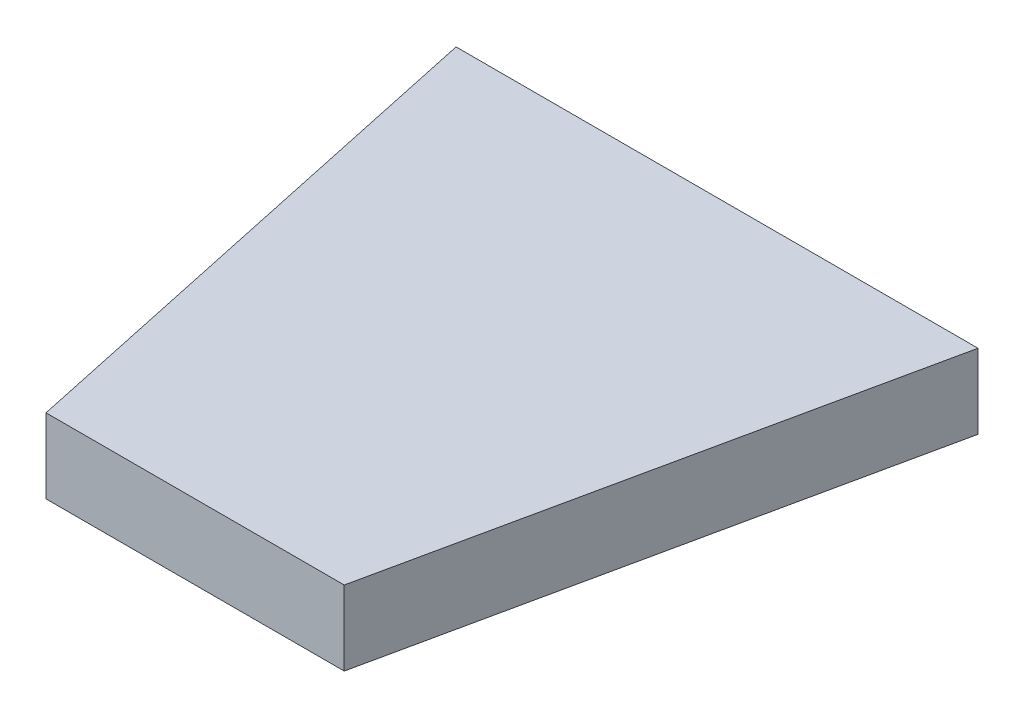
SolidWorks part; units mm, degrees
ref_plane "Front Plane" through (0, 0, 0) normal (0, 0, 1) x (1, 0, 0)
ref_plane "Top Plane" through (0, 0, 0) normal (0, 1, 0) x (1, 0, 0)
ref_plane "Right Plane" through (0, 0, 0) normal (1, 0, 0) x (0, 0, -1)
sketch "Sketch1" plane through (0, 0, 0) normal (0, 1, 0) x (1, 0, 0)
  line L0 (-35, 35) -> (-20, -35)
  line L1 (-20, -35) -> (20, -35)
  line L2 (20, -35) -> (35, 35)
  line L3 (35, 35) -> (-35, 35)
  line L4 (0, 35) -> (0, -35) construction
  point P7 (0, 0)
  point P8 (0, 0)
  dimension "D1" = 70
  dimension "D2" = 40
  dimension "D3" = 70
extrude "Boss-Extrude1" add sketch "Sketch1" along normal blind 10
